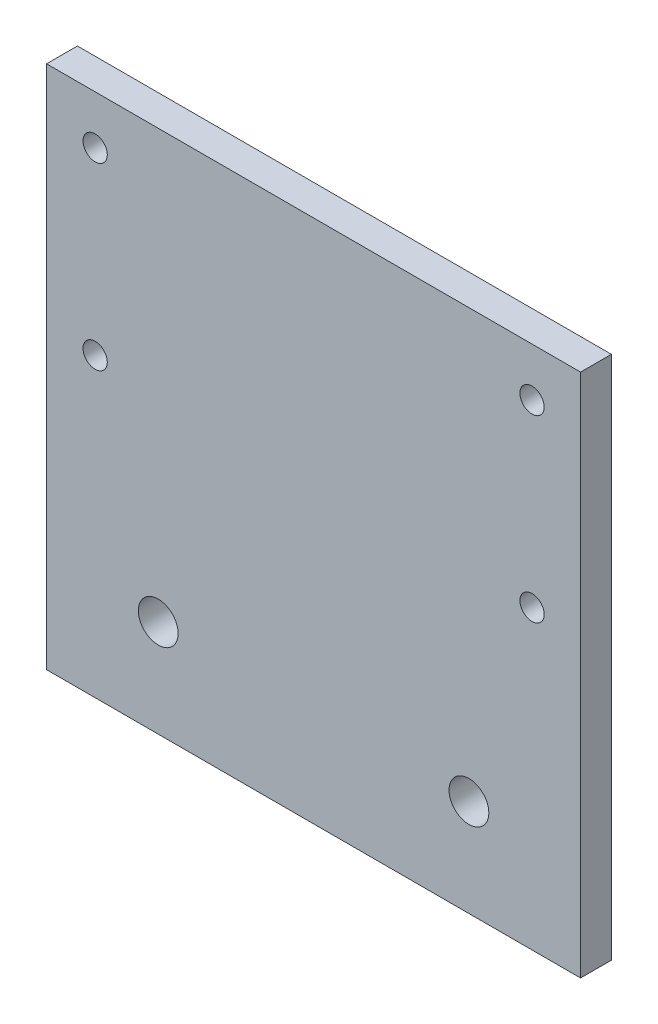
SolidWorks part; units mm, degrees
ref_plane "Front Plane" through (0, 0, 0) normal (0, 0, 1) x (1, 0, 0)
ref_plane "Top Plane" through (0, 0, 0) normal (0, 1, 0) x (1, 0, 0)
ref_plane "Right Plane" through (0, 0, 0) normal (1, 0, 0) x (0, 0, -1)
sketch "Sketch1" plane through (0, 0, 0) normal (0, 0, 1) x (1, 0, 0)
  line L0 (27.5, 54.05) -> (27.5, 0) construction
  line L1 (0, 0) -> (55, 0)
  line L2 (0, 0) -> (0, 54.05)
  line L3 (0, 54.05) -> (55, 54.05)
  line L4 (55, 0) -> (55, 54.05)
  line L5 (5, 49.05) -> (50, 49.05) construction
  line L6 (5, 49.05) -> (5, 30.55) construction
  line L7 (5, 30.55) -> (50, 30.55) construction
  line L8 (50, 49.05) -> (50, 30.55) construction
  line L9 (11.5, 10) -> (43.5, 10) construction
  circle A0 centre (5, 49.05) radius 1.25
  circle A1 centre (50, 49.05) radius 1.25
  circle A2 centre (50, 30.55) radius 1.25
  circle A3 centre (5, 30.55) radius 1.25
  circle A4 centre (11.5, 10) radius 2.05
  circle A5 centre (43.5, 10) radius 2.05
  point P11 (27.5, 49.05)
  point P23 (27.5, 10)
  dimension "D6" = 2.5
  dimension "D9" = 4.1
  dimension "D10" = 4.1
  dimension "D1" = 55
  dimension "D2" = 54.05
  dimension "D3" = 45
  dimension "D4" = 18.5
  dimension "D5" = 5
  dimension "D11" = 32
  dimension "D12" = 20
  dimension "D7" = 2
  dimension "D8" = 2
extrude "Boss-Extrude1" add sketch "Sketch1" along normal blind 3.175
